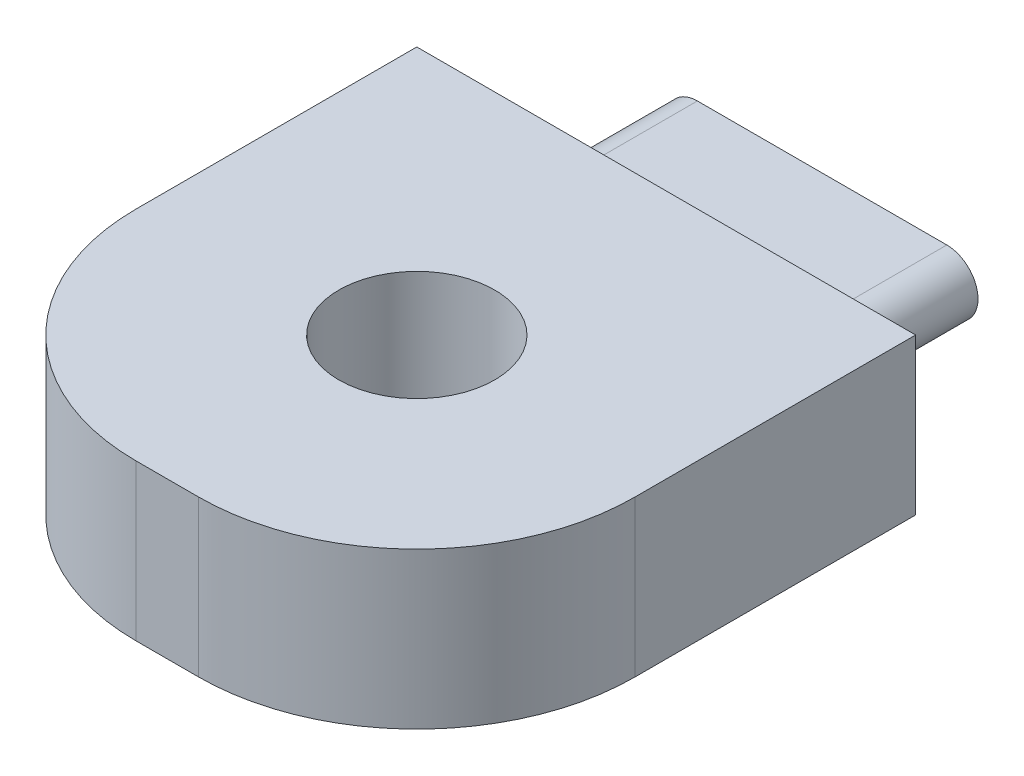
SolidWorks part; units mm, degrees
material "1060 Alloy"
ref_plane "Front Plane" through (0, 0, 0) normal (0, 0, 1) x (1, 0, 0)
ref_plane "Top Plane" through (0, 0, 0) normal (0, 1, 0) x (1, 0, 0)
ref_plane "Right Plane" through (0, 0, 0) normal (1, 0, 0) x (0, 0, -1)
sketch "Sketch1" plane through (0, 0, 0) normal (0, 1, 0) x (1, 0, 0)
  line L2 (-8, 0) -> (-8, -9)
  line L3 (-1, -16) -> (1, -16)
  line L4 (8, 0) -> (8, -9)
  line L5 (-44.2539, 0) -> (44.2539, 0) construction
  line L13 (8, 0) -> (-8, 0)
  line L14 (0, -44.7868) -> (0, 44.7868) construction
  arc A0 (1, -16) -> (8, -9) centre (1, -9) ccw
  arc A1 (-8, -9) -> (-1, -16) centre (-1, -9) ccw
  circle A2 centre (0, -8) radius 2.5
  point P0 (0, 0)
  point P2 (0, 0)
  point P13 (8, -16)
  point P16 (-8, -16)
  dimension "D3" = 7
  dimension "D4" = 5
  dimension "D1" = 16
  dimension "D2" = 16
  dimension "D5" = 8
extrude "Boss-Extrude1" add sketch "Sketch1" along normal blind 5
sketch "Sketch2" plane through (0, 0, 0) normal (0, 0, -1) x (-1, 0, 0)
  line L0 (-4, 2) -> (4, 2) construction
  line L1 (0, 44.7868) -> (0, -44.7868) construction
  line L2 (-4, 3) -> (4, 3)
  line L3 (-4, 1) -> (4, 1)
  line L4 (55, 0) -> (-55, 0) construction
  arc A0 (-4, 3) -> (-4, 1) centre (-4, 2) ccw
  arc A1 (4, 1) -> (4, 3) centre (4, 2) ccw
  point P4 (0, 2)
  dimension "D2" = 1
  dimension "D1" = 8
  dimension "D3" = 2
extrude "Boss-Extrude2" add sketch "Sketch2" along normal blind 5
